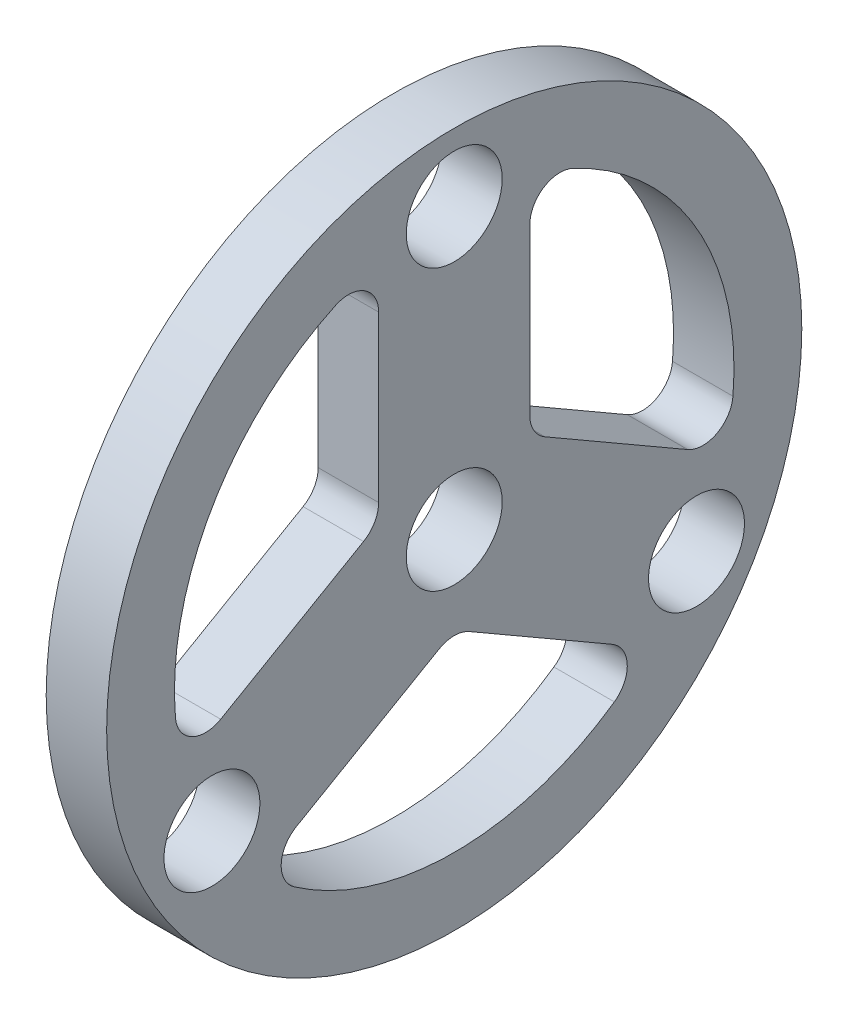
SolidWorks part; units mm, degrees
ref_plane "Front Plane" through (0, 0, 0) normal (0, 0, 1) x (1, 0, 0)
ref_plane "Top Plane" through (0, 0, 0) normal (0, 1, 0) x (1, 0, 0)
ref_plane "Right Plane" through (0, 0, 0) normal (1, 0, 0) x (0, 0, -1)
sketch "Sketch1" plane through (0, 0, 0) normal (1, 0, 0) x (0, 0, -1)
  line L0 (0, 0) -> (0, 1.0694) construction
  line L1 (0, 0) -> (0, 18.5125) construction
  line L2 (6, 2.3094) -> (15.4517, -3.1476)
  line L3 (-5, 4.0415) -> (-5, 14.9554)
  line L4 (5, 4.0415) -> (5, 14.9554)
  line L5 (-1, -6.3509) -> (-10.4517, -11.8078)
  line L6 (0, 0) -> (0.9261, -0.5347) construction
  line L7 (0, 0) -> (16.0323, -9.2563) construction
  line L8 (-6, 2.3094) -> (-15.4517, -3.1476)
  line L9 (1, -6.3509) -> (10.4517, -11.8078)
  line L10 (0, 0) -> (-0.9261, -0.5347) construction
  line L11 (0, 0) -> (-16.0323, -9.2562) construction
  line L12 (-5, 0) -> (-5, 18.5125) construction
  line L13 (5, 0) -> (5, 18.5125) [skipped]
  line L15 (2.5, 4.3301) -> (18.5323, -4.9261) [skipped]
  line L16 (-2.5, -4.3301) -> (13.5323, -13.5864) [skipped]
  line L17 (2.5, -4.3301) -> (-13.5323, -13.5864) [skipped]
  circle A0 centre (0, 0) radius 3.175
  circle A1 centre (0, 18.5125) radius 1.5875 construction
  circle A2 centre (0, 18.5125) radius 3.175
  circle A3 centre (0, 0) radius 23
  circle A4 centre (16.0323, -9.2563) radius 3.175
  circle A5 centre (16.0323, -9.2563) radius 1.5875 construction
  circle A6 centre (-16.0323, -9.2562) radius 3.175
  circle A7 centre (-16.0323, -9.2562) radius 1.5875 construction
  arc A8 (-7.8478, 16.7668) -> (-18.4444, -1.5869) centre (0, 0) ccw
  arc A9 (5, 4.0415) -> (6, 2.3094) centre (7, 4.0415) ccw
  circle A10 centre (0, 0) radius 20.1 construction
  circle A11 centre (0, 0) radius 18.5125 construction
  arc A12 (15.4517, -3.1476) -> (18.4444, -1.5869) centre (16.4517, -1.4155) ccw
  arc A13 (-15.4517, -3.1476) -> (-18.4444, -1.5869) centre (-16.4517, -1.4155) cw
  arc A14 (-6, 2.3094) -> (-5, 4.0415) centre (-7, 4.0415) ccw
  arc A15 (-5, 14.9554) -> (-7.8478, 16.7668) centre (-7, 14.9554) ccw
  arc A16 (18.4444, -1.5869) -> (7.8478, 16.7668) centre (0, 0) ccw
  arc A17 (5, 14.9554) -> (7.8478, 16.7668) centre (7, 14.9554) cw
  arc A18 (1, -6.3509) -> (-1, -6.3509) centre (0, -8.0829) ccw
  arc A19 (-10.4517, -11.8078) -> (-10.5965, -15.1798) centre (-9.4517, -13.5399) ccw
  arc A20 (-10.5965, -15.1798) -> (10.5965, -15.1798) centre (0, 0) ccw
  arc A21 (10.4517, -11.8078) -> (10.5965, -15.1798) centre (9.4517, -13.5399) cw
  dimension "D1" = 3
  dimension "D2" = 3.175
  dimension "D3" = 6.35
  dimension "D4" = 46
  dimension "D5" = 40.2
  dimension "D6" = 37.025
  dimension "D7" = 3
  dimension "D8" = 2
extrude "Boss-Extrude1" add sketch "Sketch1" along normal blind 4
